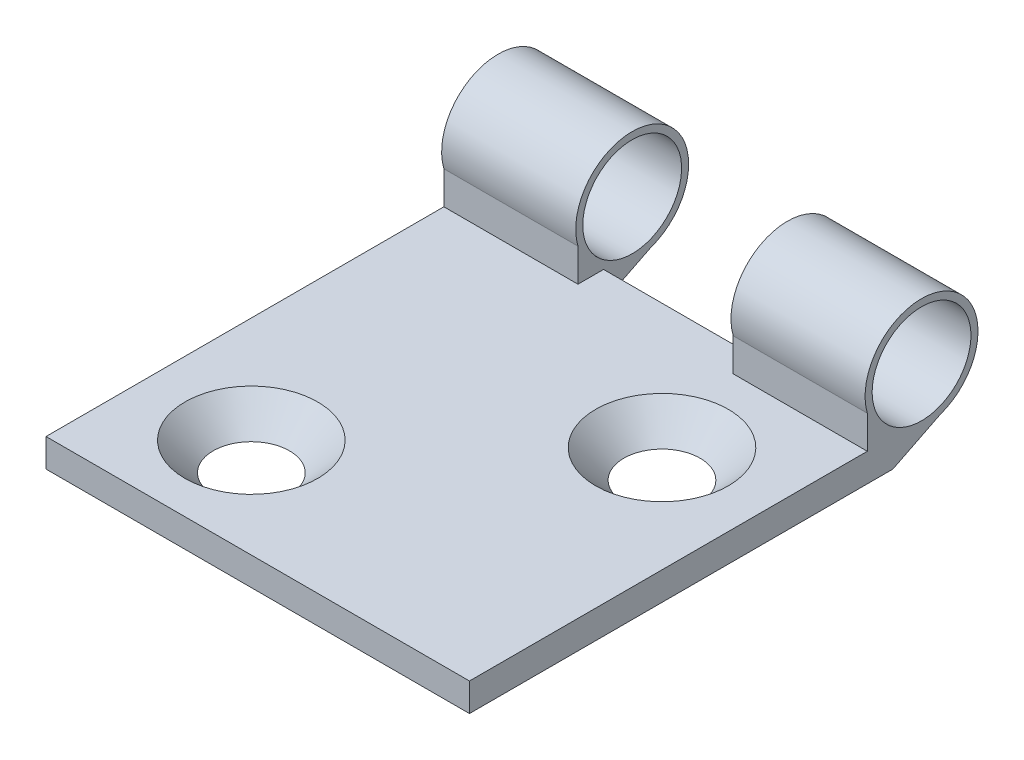
SolidWorks part; units mm, degrees
ref_plane "Front" through (0, 0, 0) normal (0, 0, 1) x (1, 0, 0)
ref_plane "Top" through (0, 0, 0) normal (0, 1, 0) x (1, 0, 0)
ref_plane "Right" through (0, 0, 0) normal (1, 0, 0) x (0, 0, -1)
sketch "Эскиз1" plane through (0, 0, 0) normal (0, 1, 0) x (1, 0, 0)
  line L1 (-85.3326, -39.6061) -> (-55.3326, -39.6061)
  line L2 (-85.3326, -39.6061) -> (-85.3326, -69.6061)
  line L3 (-85.3326, -69.6061) -> (-55.3326, -69.6061)
  line L4 (-55.3326, -39.6061) -> (-55.3326, -69.6061)
  dimension "D1" = 30
  dimension "D2" = 30
extrude "Бобышка-Вытянуть1" add sketch "Эскиз1" along normal blind 2
ref_plane "Плоскость1" through (-64.8326, 0, 0) normal (-1, 0, 0) x (0, 0, 1)
sketch "Эскиз2" plane through (-85.3326, 0, 0) normal (-1, 0, 0) x (0, 0, 1)
  circle A0 centre (37.5773, 5.4473) radius 4
  dimension "D1" = 8
extrude "Бобышка-Вытянуть2" add sketch "Эскиз2" against normal blind 9.5 separate body
sketch "Эскиз3" plane through (-64.8326, 0, 0) normal (-1, 0, 0) x (0, 0, 1)
  circle A0 centre (37.5773, 5.4473) radius 4
  circle A1 centre (37.5773, 5.4473) radius 4 construction
extrude "Бобышка-Вытянуть3" add sketch "Эскиз3" against normal blind 9.5 separate body
sketch "Эскиз4" plane through (-85.3326, 0, 0) normal (-1, 0, 0) x (0, 0, 1)
  circle A0 centre (37.5773, 5.4473) radius 3.5
  circle A1 centre (37.5773, 5.4473) radius 4 construction
  dimension "D1" = 7
extrude "Вырез-Вытянуть1" cut sketch "Эскиз4" against normal up to surface (30 mm away)
sketch "Эскиз5" plane through (-85.3326, 0, 0) normal (-1, 0, 0) x (0, 0, 1)
  line L0 (39.6061, 0) -> (36.267, 1.668)
  line L2 (39.6061, 0) -> (41.4182, 0)
  line L3 (39.6061, 0) -> (69.6061, 0) construction
  line L4 (41.4182, 0) -> (41.4182, 4.3305)
  circle A0 centre (37.5773, 5.4473) radius 4 construction
  arc A2 (36.267, 1.668) -> (41.4182, 4.3305) centre (37.5773, 5.4473) ccw
extrude "Бобышка-Вытянуть4" add sketch "Эскиз5" against normal blind 9.5
sketch "Эскиз6" plane through (-64.8326, 0, 0) normal (-1, 0, 0) x (0, 0, 1)
  line L0 (41.4182, 2) -> (41.4182, 4.3305) construction
  line L1 (41.4182, 2) -> (41.4182, 4.3305)
  line L2 (36.267, 1.668) -> (39.6061, 0) construction
  line L3 (36.267, 1.668) -> (39.6061, 0)
  line L4 (41.4182, 2) -> (39.6061, 0)
  line L5 (36.267, 1.668) -> (36.6368, 2.076)
  line L6 (41.4182, 4.3305) -> (40.8391, 4.1782)
  circle A0 centre (37.5773, 5.4473) radius 3.5 construction
  arc A1 (36.6368, 2.076) -> (40.8391, 4.1782) centre (37.5773, 5.4473) ccw
extrude "Бобышка-Вытянуть5" add sketch "Эскиз6" against normal blind 9.5
hole_wizard "Зенковка для  винта с плоской головкой M41" positions "Эскиз7" profile "Эскиз8" countersink size "M4" standard "Ansi Metric"
sketch "Эскиз7" plane through (0, 2, 0) normal (0, 1, 0) x (1, 0, 0)
  line L0 (-70.3326, -39.6061) -> (-70.3326, -69.6061) construction
  line L1 (-64.8326, -39.6061) -> (-75.8326, -39.6061) construction
  line L2 (-85.3326, -69.6061) -> (-55.3326, -69.6061) construction
  line L4 (-85.3326, -55.5122) -> (-55.3326, -55.5122) construction
  line L5 (-85.3326, -41.4182) -> (-85.3326, -69.6061) construction
  line L6 (-55.3326, -69.6061) -> (-55.3326, -41.4182) construction
  line L8 (-55.3326, -41.4182) -> (-70.3326, -55.5122) construction
  line L10 (-70.3326, -55.5122) -> (-85.3326, -69.6061) construction
  point P0 (-62.8326, -48.4652)
  point P2 (-77.8326, -62.5591)
  point P30 (0, 0)
  point P31 (-77.8326, -62.5591)
  point P32 (0, 0)
  point P34 (0, 0)
  point P35 (-62.8326, -48.4652)
sketch "Эскиз8" plane through (-62.8326, 2, 48.4652) normal (1, 0, 0) x (0, 0, 1)
  line L0 (0, 0) -> (0, 22.3519)
  line L1 (0, 22.3519) -> (2.25, 21)
  line L2 (2.25, 21) -> (2.25, 2.45)
  line L3 (2.25, 2.45) -> (4.7, 0)
  line L5 (4.7, 0) -> (0, 0)
  line L6 (-2.25, 2.45) -> (-4.7, 0) construction
  line L10 (0, 22.3519) -> (-2.25, 21) construction
  line L11 (0, -6.35) -> (0, 107.95) construction
  dimension "Диаметр отверстия" = 4.5
  dimension "Глубина отверстия" = 21
  dimension "Диаметр передней зенковки" = 9.4
  dimension "Угол передней зенковки" = 90
  dimension "Угол заточки сверла" = 118
